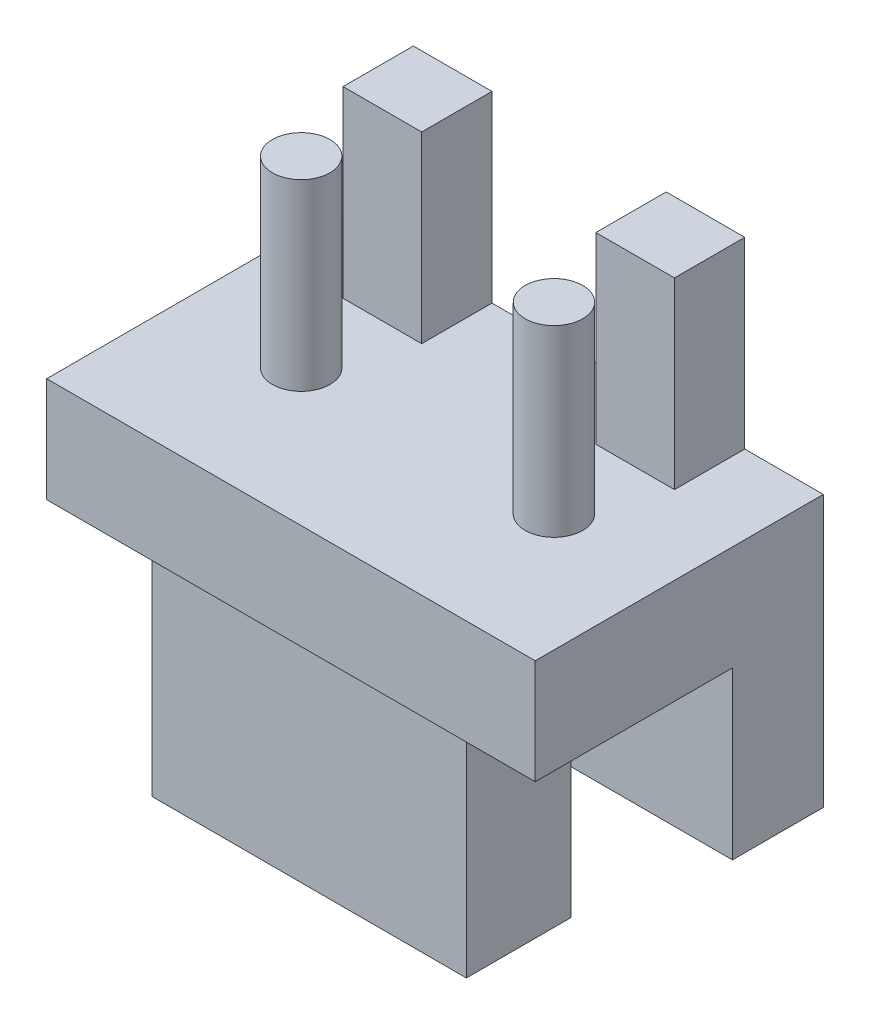
SolidWorks part; units mm, degrees
ref_plane "Front Plane" through (0, 0, 0) normal (0, 0, 1) x (1, 0, 0)
ref_plane "Top Plane" through (0, 0, 0) normal (0, 1, 0) x (1, 0, 0)
ref_plane "Right Plane" through (0, 0, 0) normal (1, 0, 0) x (0, 0, -1)
sketch "Sketch1" plane through (0, 0, 0) normal (0, 1, 0) x (1, 0, 0)
  line L1 (0, 0) -> (16.5, 0)
  line L2 (0, 0) -> (0, 11.5)
  line L3 (0, 11.5) -> (16.5, 11.5)
  line L4 (16.5, 0) -> (16.5, 11.5)
  line L5 (3, 3) -> (13.5, 3)
  line L6 (3, 3) -> (3, 8.5)
  line L7 (3, 8.5) -> (13.5, 8.5)
  line L8 (13.5, 3) -> (13.5, 8.5)
  point P9 (3, 5.75)
  point P10 (0, 5.75)
  point P11 (8.25, 3)
  point P12 (8.25, 0)
  dimension "D1" = 10.5
  dimension "D2" = 5.5
  dimension "D3" = 3
  dimension "D4" = 3
extrude "Boss-Extrude1" add sketch "Sketch1" along normal blind 17
sketch "Sketch2" plane through (0, 0, -11.5) normal (0, 0, -1) x (-1, 0, 0)
  line L0 (-16.5, 17) -> (0, 17) construction
  circle A0 centre (-8.25, 10.5) radius 2.5
  point P2 (0, 0)
  point P5 (-8.25, 17)
  dimension "D1" = 5
  dimension "D2" = 6.5
extrude "Cut-Extrude1" cut sketch "Sketch2" against normal up to next
sketch "Sketch3" plane through (0, 17, 0) normal (0, 1, 0) x (1, 0, 0)
  line L1 (0, 11.5) -> (16.5, 11.5)
  line L2 (0, 11.5) -> (0, 0)
  line L3 (0, 0) -> (16.5, 0)
  line L4 (16.5, 11.5) -> (16.5, 0)
extrude "Boss-Extrude2" add sketch "Sketch3" along normal blind 3
sketch "Sketch4" plane through (0, 20, 0) normal (0, 1, 0) x (1, 0, 0)
  line L0 (16.5, 11.5) -> (0, 11.5) construction
  line L1 (-21.75, -7.676) -> (0, -7.676)
  line L2 (-21.75, -7.676) -> (-21.75, 0.324)
  line L3 (-21.75, 0.324) -> (0, 0.324)
  line L4 (0, -7.676) -> (0, 0.324)
  line L6 (0, 0) -> (16.5, 0) construction
  line L7 (0, 11.5) -> (0, 0) construction
  line L9 (-21.75, 0.324) -> (0, 0.324)
  line L10 (-21.75, 0.324) -> (-21.75, 3.324)
  line L11 (-21.75, 3.324) -> (0, 3.324)
  line L12 (0, 0.324) -> (0, 3.324)
  point P8 (8.25, 0)
  line M5 (0, 11.5) -> (0, 0)
  dimension "D1" = 11.176
  dimension "D2" = 30
  dimension "D3" = 8
  dimension "D4" = 3
extrude "Boss-Extrude3" add sketch "Sketch4" along normal blind 4 from offset 11 contours L11 L10 L3 M5 | L1 L4 L3 L2 M5 offset against normal yes
chamfer "Chamfer1" distance 5 angle 45 2 edges at (0, 11, 0) (0, 11, -3.324)
chamfer "Chamfer2" distance 3 angle 45 4 edges at (0, 9, -4.162) (0, 13, -4.162) (2.5, 9, 0) (2.5, 13, 0)
sketch "Sketch5" plane through (0, 13, 0) normal (0, 1, 0) x (1, 0, 0)
  line L1 (-20.65, 3.324) -> (-17.65, 3.324)
  line L2 (-20.65, 3.324) -> (-20.65, 0.64)
  line L3 (-20.65, 0.64) -> (-17.65, 0.64)
  line L4 (-17.65, 3.324) -> (-17.65, 0.64)
  line L6 (-11, 3.324) -> (-8, 3.324)
  line L7 (-11, 3.324) -> (-11, 0.64)
  line L8 (-11, 0.64) -> (-8, 0.64)
  line L9 (-8, 3.324) -> (-8, 0.64)
  line L10 (-21.4804, -11.36) -> (-3.4221, -11.36) construction
  line L11 (16.5, 11.5) -> (0, 11.5) construction
  line L12 (-3, -3) -> (-3, 5.324) construction
  line L13 (-21.75, 3.324) -> (-5, 3.324) construction
  circle A0 centre (-19.15, -2.46) radius 1.1
  circle A1 centre (-9.5, -2.46) radius 1.1
  point P15 (-19.15, 0.64)
  point P16 (-9.5, 0.64)
  dimension "D1" = 2.2
  dimension "D2" = 3
  dimension "D3" = 3.1
  dimension "D4" = 3.1
  dimension "D5" = 3
  dimension "D6" = 5
  dimension "D7" = 9.65
  dimension "D8" = 12
  dimension "D9" = 22.86
extrude "Boss-Extrude4" add sketch "Sketch5" along normal blind 7
sketch "Sketch6" plane through (0, 0, 7.676) normal (0, 0, 1) x (1, 0, 0)
  line L0 (-21.75, 13) -> (-24.65, 13)
  line L1 (-24.65, 13) -> (-24.65, 20)
  line L2 (-24.65, 20) -> (-27.65, 20)
  line L3 (-27.65, 20) -> (-27.65, 9)
  line L4 (-27.65, 9) -> (-21.75, 9)
  line L5 (-18.05, 20) -> (-20.25, 20) construction
  line L6 (-18.05, 20) -> (-20.25, 20) construction
  line L11 (-21.75, 9) -> (0, 9)
  line L12 (0, 9) -> (0, 13)
  line L13 (0, 13) -> (-21.75, 13)
  line L14 (-21.75, 13) -> (-21.75, 9)
  line L18 (-21.75, 13) -> (-21.75, 9)
  point P4 (0, 0)
  point P11 (-19.15, 20)
  point P12 (0, 0)
  dimension "D1" = 5.5
  dimension "D2" = 3
  dimension "D3" = 0
extrude "Boss-Extrude5" add sketch "Sketch6" against normal up to surface (11 mm away) up to face at (-14.0083, 14.6667, -3.324)
sketch "Sketch7" plane through (0, 0, -11.5) normal (0, 0, -1) x (-1, 0, 0)
  line L0 (-3, 17) -> (-13.5, 17) construction
  line L1 (-13.5, 17) -> (-3, 17)
  line L2 (-13.5, 17) -> (-13.5, 15.5)
  line L3 (-13.5, 15.5) -> (-3, 15.5)
  line L4 (-3, 17) -> (-3, 15.5)
  line L5 (-13.5, 17) -> (-13.5, 0) construction
  line L6 (-3, 17) -> (-3, 0) construction
  dimension "D1" = 1.5
extrude "Cut-Extrude2" cut sketch "Sketch7" against normal up to next
sketch "Sketch8" plane through (0, 20, 0) normal (0, 1, 0) x (1, 0, 0)
  line L0 (-24.65, -7.676) -> (0, -7.676) construction
  line L1 (16.5, 11.5) -> (-5, 11.5)
  line L2 (16.5, 11.5) -> (16.5, -7.676)
  line L3 (16.5, -7.676) -> (-5, -7.676)
  line L4 (-5, 11.5) -> (-5, -7.676)
  line L6 (-27.65, 3.324) -> (-23.65, 3.324)
  line L7 (-27.65, 3.324) -> (-27.65, -7.676)
  line L8 (-27.65, -7.676) -> (-23.65, -7.676)
  line L9 (-23.65, 3.324) -> (-23.65, -7.676)
  dimension "D1" = 4
extrude "Cut-Extrude3" cut sketch "Sketch8" against normal up to next
sketch "Sketch9" plane through (0, 9, 0) normal (0, -1, 0) x (1, 0, 0)
  line L0 (-19.15, 2.46) -> (-9.5, 2.46) construction
  line L1 (-20.325, 6.978) -> (-8.325, 6.978)
  line L2 (-20.325, 6.978) -> (-20.325, 2.978)
  line L3 (-20.325, 2.978) -> (-8.325, 2.978)
  line L4 (-8.325, 6.978) -> (-8.325, 2.978)
  line L5 (-23.65, 7.676) -> (-5, 7.676) construction
  circle A0 centre (-9.5, 2.46) radius 1.1 construction
  circle A1 centre (-19.15, 2.46) radius 1.1 construction
  circle A2 centre (-9.5, 2.46) radius 1.1 construction
  circle A3 centre (-19.15, 2.46) radius 1.1 construction
  point P10 (-14.325, 6.978)
  point P11 (-14.325, 2.46)
  dimension "D1" = 12
  dimension "D2" = 4
  dimension "D3" = 0.698
extrude "Boss-Extrude6" add sketch "Sketch9" along normal blind 8.5
sketch "Sketch10" plane through (0, 9, 0) normal (0, -1, 0) x (1, 0, 0)
  line L0 (-5, 7.676) -> (-5, -3.324) construction
  line L1 (-23.65, -3.324) -> (-5, -3.324)
  line L2 (-23.65, -3.324) -> (-23.65, 0.146)
  line L3 (-23.65, 0.146) -> (-5, 0.146)
  line L4 (-5, -3.324) -> (-5, 0.146)
  dimension "D1" = 3.47
extrude "Boss-Extrude7" add sketch "Sketch10" along normal blind 6.35
